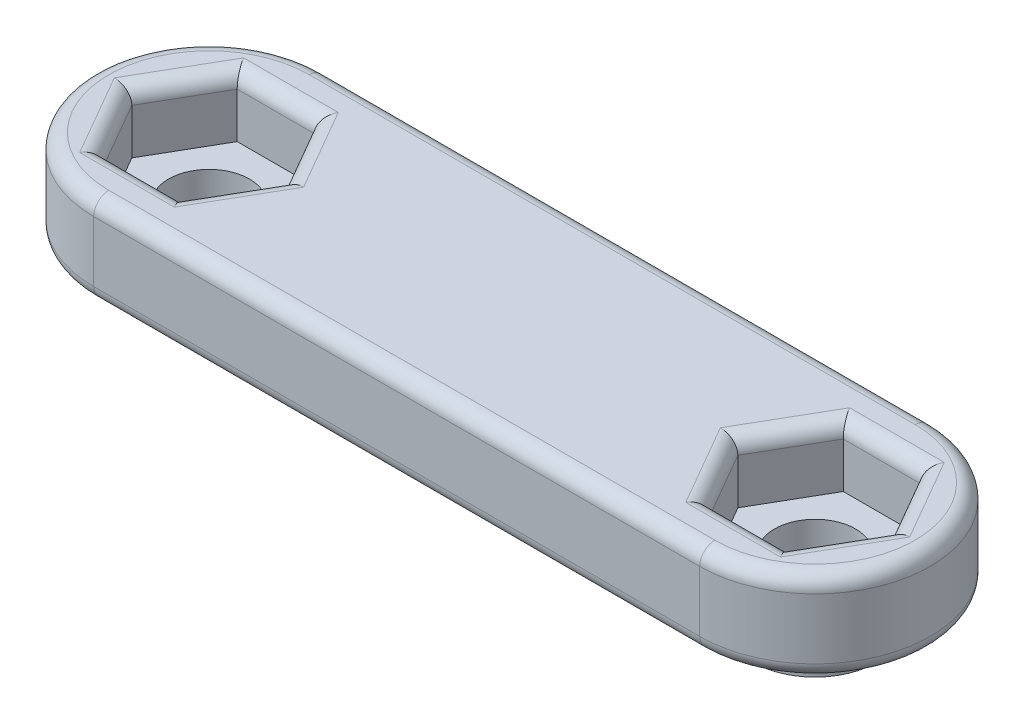
SolidWorks part; units mm, degrees
ref_plane "Front Plane" through (0, 0, 0) normal (0, 0, 1) x (1, 0, 0)
ref_plane "Top Plane" through (0, 0, 0) normal (0, 1, 0) x (1, 0, 0)
ref_plane "Right Plane" through (0, 0, 0) normal (1, 0, 0) x (0, 0, -1)
sketch "Sketch1" plane through (0, 0, 0) normal (0, 1, 0) x (1, 0, 0)
  line L2 (-15.875, 0) -> (15.875, 0) construction
  line L3 (-13.8543, 3.5) -> (-17.8957, 3.5)
  line L4 (-15.875, 6.04) -> (15.875, 6.04)
  line L5 (17.8957, 3.5) -> (13.8543, 3.5)
  line L8 (-15.875, -6.04) -> (15.875, -6.04)
  line L9 (13.8543, 3.5) -> (11.8335, 0)
  line L10 (11.8335, 0) -> (13.8543, -3.5)
  line L11 (13.8543, -3.5) -> (17.8957, -3.5)
  line L12 (17.8957, -3.5) -> (19.9165, 0)
  line L13 (19.9165, 0) -> (17.8957, 3.5)
  line L14 (-17.8957, 3.5) -> (-19.9165, 0)
  line L15 (-19.9165, 0) -> (-17.8957, -3.5)
  line L16 (-17.8957, -3.5) -> (-13.8543, -3.5)
  line L17 (-13.8543, -3.5) -> (-11.8335, 0)
  line L18 (-11.8335, 0) -> (-13.8543, 3.5)
  arc A12 (-15.875, -6.04) -> (-15.875, 6.04) centre (-15.875, 0) cw
  arc A18 (15.875, -6.04) -> (15.875, 6.04) centre (15.875, 0) ccw
  circle A19 centre (15.875, 0) radius 3.5 construction
  circle A24 centre (-15.875, 0) radius 3.5 construction
  point P1 (0, 0)
  dimension "D2" = 31.75
  dimension "D3" = 12.08
  dimension "D11" = 7
extrude "Boss-Extrude1" add sketch "Sketch1" along normal blind 4.5
sketch "Sketch2" plane through (0, 4.5, 0) normal (0, 1, 0) x (1, 0, 0)
  line L0 (-17.8957, 3.5) -> (-19.9165, 0) construction
  line L1 (19.9165, 0) -> (17.8957, 3.5) construction
  line L2 (17.8957, -3.5) -> (19.9165, 0) construction
  line L3 (13.8543, -3.5) -> (17.8957, -3.5) construction
  line L4 (15.875, 6.04) -> (-15.875, 6.04)
  line L5 (-15.875, -6.04) -> (15.875, -6.04)
  line L6 (11.8335, 0) -> (13.8543, -3.5) construction
  line L7 (13.8543, 3.5) -> (11.8335, 0) construction
  line L8 (15.875, 6.04) -> (-15.875, 6.04)
  line L9 (-15.875, -6.04) -> (15.875, -6.04)
  line L10 (17.8957, 3.5) -> (13.8543, 3.5) construction
  line L11 (19.9165, 0) -> (17.8957, 3.5)
  line L12 (17.8957, -3.5) -> (19.9165, 0)
  line L13 (13.8543, -3.5) -> (17.8957, -3.5)
  line L14 (11.8335, 0) -> (13.8543, -3.5)
  line L15 (13.8543, 3.5) -> (11.8335, 0)
  line L16 (17.8957, 3.5) -> (13.8543, 3.5)
  line L17 (-19.9165, 0) -> (-17.8957, -3.5) construction
  line L18 (-17.8957, -3.5) -> (-13.8543, -3.5) construction
  line L19 (-13.8543, -3.5) -> (-11.8335, 0) construction
  line L20 (-11.8335, 0) -> (-13.8543, 3.5) construction
  line L21 (-13.8543, 3.5) -> (-17.8957, 3.5) construction
  line L22 (-17.8957, 3.5) -> (-19.9165, 0)
  line L23 (-19.9165, 0) -> (-17.8957, -3.5)
  line L24 (-17.8957, -3.5) -> (-13.8543, -3.5)
  line L25 (-13.8543, -3.5) -> (-11.8335, 0)
  line L26 (-11.8335, 0) -> (-13.8543, 3.5)
  line L27 (-13.8543, 3.5) -> (-17.8957, 3.5)
  arc A5 (15.875, -6.04) -> (15.875, 6.04) centre (15.875, 0) ccw
  arc A6 (15.875, -6.04) -> (15.875, 6.04) centre (15.875, 0) ccw
  arc A9 (-15.875, 6.04) -> (-15.875, -6.04) centre (-15.875, 0) ccw
  arc A17 (-15.875, 6.04) -> (-15.875, -6.04) centre (-15.875, 0) ccw
  dimension "D1" = 0
extrude "Boss-Extrude2" add sketch "Sketch2" along normal offset from surface (1.5 mm away) 6 up to face at (0, 0, 0)
sketch "Sketch3" plane through (0, 0, 0) normal (0, -1, 0) x (1, 0, 0)
  line L6 (15.875, 6.04) -> (-15.875, 6.04)
  line L7 (-15.875, -6.04) -> (15.875, -6.04)
  line L10 (15.875, 6.04) -> (-15.875, 6.04)
  line L11 (-15.875, -6.04) -> (15.875, -6.04)
  arc A2 (15.875, -6.04) -> (15.875, 6.04) centre (15.875, 0) ccw
  arc A3 (15.875, -6.04) -> (15.875, 6.04) centre (15.875, 0) ccw
  arc A11 (-15.875, 6.04) -> (-15.875, -6.04) centre (-15.875, 0) ccw
  arc A17 (-15.875, 6.04) -> (-15.875, -6.04) centre (-15.875, 0) ccw
  dimension "D1" = 0
extrude "Cut-Extrude1" cut sketch "Sketch3" against normal offset from surface (1.2375 mm away) 4.7625 up to face at (15.875, 6, 0)
sketch "Sketch6" plane through (0, 1.2375, 0) normal (0, -1, 0) x (1, 0, 0)
  line L0 (13.8543, 3.5) -> (11.8335, 0) construction
  line L1 (11.8335, 0) -> (13.8543, -3.5) construction
  line L2 (13.8543, -3.5) -> (17.8957, -3.5) construction
  line L3 (17.8957, -3.5) -> (19.9165, 0) construction
  line L4 (19.9165, 0) -> (17.8957, 3.5) construction
  line L5 (17.8957, 3.5) -> (13.8543, 3.5) construction
  line L6 (13.8543, 3.5) -> (11.8335, 0)
  line L7 (11.8335, 0) -> (13.8543, -3.5)
  line L8 (13.8543, -3.5) -> (17.8957, -3.5)
  line L9 (17.8957, -3.5) -> (19.9165, 0)
  line L10 (19.9165, 0) -> (17.8957, 3.5)
  line L11 (17.8957, 3.5) -> (13.8543, 3.5)
  line L12 (17.8957, 3.5) -> (13.8543, -3.5) construction
  circle A0 centre (15.875, 0) radius 2.125
  dimension "D1" = 4.25
extrude "Boss-Extrude3" add sketch "Sketch6" against normal blind 1.5875
sketch "Sketch7" plane through (0, 1.2375, 0) normal (0, -1, 0) x (1, 0, 0)
  circle A0 centre (15.875, 0) radius 2.125
  circle A1 centre (15.875, 0) radius 3.25
  circle A2 centre (15.875, 0) radius 2.125 construction
  dimension "D1" = 6.5
extrude "Boss-Extrude4" add sketch "Sketch7" along normal blind 1.778
mirror "Mirror1" about plane through (0, 0, 0) normal (1, 0, 0) of "Boss-Extrude3", "Boss-Extrude4"
fillet "Fillet2" radius 0.7937 6 edges at (0, 1.2375, -6.04) (-21.915, 1.2375, 0) (0, 1.2375, 6.04) (21.915, 1.2375, 0) (15.875, 1.2375, -3.25) (-15.875, 1.2375, -3.25)
fillet "Fillet3" radius 0.7937 16 edges at (0, 6, 6.04) (-21.915, 6, 0) (0, 6, -6.04) (21.915, 6, 0) (18.9061, 6, -1.75) (15.875, 6, -3.5) (12.8439, 6, -1.75) (12.8439, 6, 1.75) (15.875, 6, 3.5) (18.9061, 6, 1.75) (-18.9061, 6, -1.75) (-18.9061, 6, 1.75) (-15.875, 6, 3.5) (-12.8439, 6, 1.75) (-12.8439, 6, -1.75) (-15.875, 6, -3.5)
